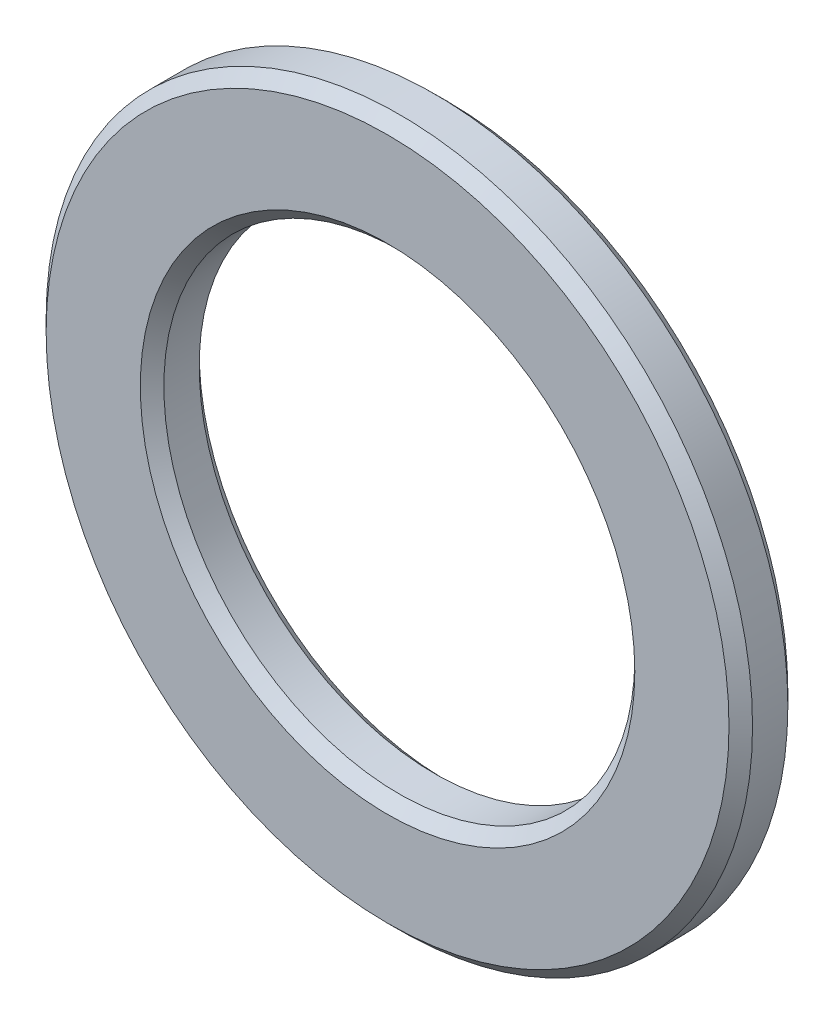
SolidWorks part; units mm, degrees
ref_plane "前视基准面" through (0, 0, 0) normal (0, 0, 1) x (1, 0, 0)
ref_plane "上视基准面" through (0, 0, 0) normal (0, 1, 0) x (1, 0, 0)
ref_plane "右视基准面" through (0, 0, 0) normal (1, 0, 0) x (0, 0, -1)
sketch "草图1" plane through (0, 0, 0) normal (0, 0, 1) x (1, 0, 0)
  circle A0 centre (0, 0) radius 2
  circle A1 centre (0, 0) radius 3
  dimension "D1" = 4
  dimension "D2" = 6
extrude "凸台-拉伸1" add sketch "草图1" along normal mid plane 0.5
chamfer "倒角1" distance 0.1 angle 45 4 edges at (2, 0, 0.25) (2, 0, -0.25) (3, 0, -0.25) (3, 0, 0.25)
